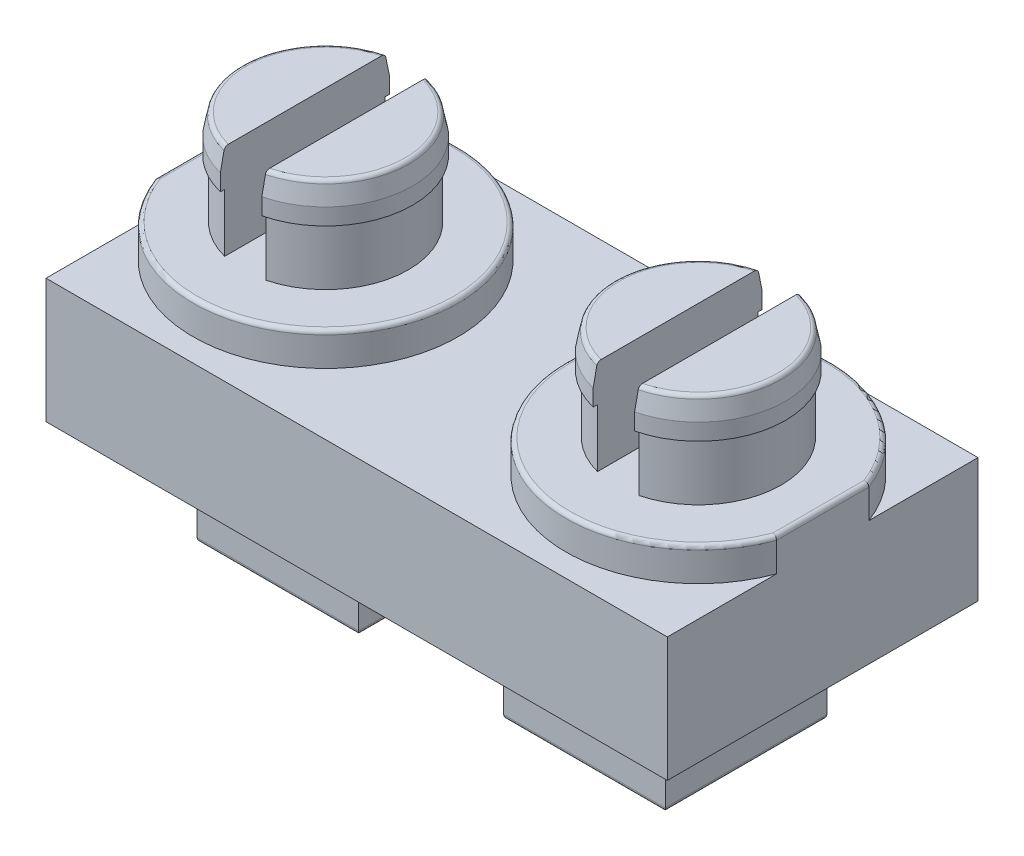
SolidWorks part; units mm, degrees
ref_plane "前视基准面" through (0, 0, 0) normal (0, 0, 1) x (1, 0, 0)
ref_plane "上视基准面" through (0, 0, 0) normal (0, 1, 0) x (1, 0, 0)
ref_plane "右视基准面" through (0, 0, 0) normal (1, 0, 0) x (0, 0, -1)
sketch "草图1" plane through (0, 0, 0) normal (0, 1, 0) x (1, 0, 0)
  line L0 (0, 0) -> (7.5, 0) construction
  line L1 (0, -3.75) -> (0, 3.75)
  line L2 (0, 3.75) -> (7.5, 3.75)
  line L3 (7.5, 3.75) -> (7.5, -3.75)
  line L4 (0, -3.75) -> (7.5, -3.75)
  dimension "D1" = 7.5
  dimension "D2" = 3.75
extrude "凸台-拉伸1" add sketch "草图1" along normal blind 3
sketch "草图3" plane through (0, 0, 3.75) normal (0, 0, 1) x (1, 0, 0)
  line L0 (0, 0) -> (3.7, 0) construction
  line L1 (0, 0) -> (7.5, 0) construction
  line L2 (3.7, 0) -> (3.7, -2) construction
  line L3 (3.7, -2) -> (3.7, -2.5) construction
  line L4 (5.2, 0) -> (2.2, 0)
  line L5 (2.2, 0) -> (2.2, -0.6771)
  line L6 (5.65, -2.5) -> (1.75, -2.5)
  line L7 (1.75, -2.5) -> (1.75, -1.5556)
  line L8 (5.65, -2.5) -> (5.65, -1.5556)
  line L9 (5.2, 0) -> (5.2, -0.6771)
  arc A0 (2.2, -0.6771) -> (1.75, -1.5556) centre (3.7, -2) ccw
  arc A1 (5.65, -1.5556) -> (5.2, -0.6771) centre (3.7, -2) ccw
  dimension "D1" = 3.7
  dimension "D2" = 2
  dimension "D3" = 0.5
  dimension "D4" = 1.5
  dimension "D5" = 1.95
extrude "凸台-拉伸2" add sketch "草图3" against normal blind 7.5
sketch "草图4" plane through (7.5, 0, 0) normal (1, 0, 0) x (0, 0, -1)
  line L0 (0, 0) -> (0, -2) construction
  line L1 (0, -2) -> (0, -2.5) construction
  line L2 (3.75, -2.5) -> (-3.75, -2.5) construction
  line L3 (1.5, 0) -> (3.75, 0)
  line L4 (-3.75, 0) -> (3.75, 0) construction
  line L5 (-1.5, 0) -> (-1.5, -0.6771)
  line L7 (-1.95, -2.5) -> (-1.95, -1.5556)
  line L8 (1.95, -2.5) -> (1.95, -1.5556)
  line L9 (1.5, 0) -> (1.5, -0.6771)
  line L10 (1.95, -2.5) -> (3.75, -2.5)
  line L11 (-3.75, 0) -> (-1.5, 0)
  line L12 (-3.75, 0) -> (-3.75, -2.5)
  line L13 (-3.75, -2.5) -> (-1.95, -2.5)
  line L14 (3.75, 0) -> (3.75, -2.5)
  arc A0 (-1.5, -0.6771) -> (-1.95, -1.5556) centre (0, -2) ccw
  arc A1 (1.95, -1.5556) -> (1.5, -0.6771) centre (0, -2) ccw
  dimension "D1" = 2
  dimension "D2" = 1.5
  dimension "D3" = 1.95
extrude "切除-拉伸1" cut sketch "草图4" against normal blind 7.5
sketch "草图5" plane through (0, 3, 0) normal (0, 1, 0) x (1, 0, 0)
  line L0 (0, 0) -> (4.5, 0) construction
  circle A0 centre (4.5, 0) radius 3.2
  dimension "D2" = 6.4
  dimension "D1" = 4.5
extrude "凸台-拉伸3" add sketch "草图5" along normal blind 0.8
sketch "草图6" plane through (0, 3.8, 0) normal (0, 1, 0) x (1, 0, 0)
  circle A0 centre (4.5, 0) radius 2
  dimension "D1" = 4
extrude "凸台-拉伸4" add sketch "草图6" along normal blind 2.3
sketch "草图7" plane through (0, 0, 0) normal (0, 0, 1) x (1, 0, 0)
  line L0 (2.5, 6.1) -> (2.5, 5.2)
  line L1 (2.5, 6.1) -> (2.5, 3.8) construction
  line L2 (2.5, 5.2) -> (2.4, 5.2)
  line L3 (2.4, 5.2) -> (2.4, 5.6)
  line L4 (2.4, 5.6) -> (2.5, 6.1)
  line L5 (4.5, 6.1) -> (4.5, 3.8) construction
  line L6 (6.5, 6.1) -> (2.5, 6.1) construction
  line L7 (7.7, 3.8) -> (1.3, 3.8) construction
  dimension "D1" = 0.9
  dimension "D2" = 0.1
  dimension "D3" = 0.4
revolve "旋转1" add sketch "草图7" angle 360 about L5
sketch "草图8" plane through (0, 6.1, 0) normal (0, 1, 0) x (1, 0, 0)
  line L0 (4.5, 0) -> (5, 0) construction
  line L1 (5, -3) -> (5, 3)
  line L2 (5, 3) -> (4, 3)
  line L3 (4.5, 3) -> (4.5, -3) construction
  line L4 (5, -3) -> (4, -3)
  line L5 (4, -3) -> (4, 3)
  dimension "D1" = 0.5
  dimension "D2" = 3
extrude "切除-拉伸2" cut sketch "草图8" against normal blind 2.3
sketch "草图9" plane through (0, 3, 0) normal (0, 1, 0) x (1, 0, 0)
  line L0 (7.5, 3.75) -> (7.5, -3.75)
  line L1 (7.5, -3.75) -> (8.5186, -3.75)
  line L2 (8.5186, -3.75) -> (8.5186, 3.75)
  line L3 (8.5186, 3.75) -> (7.5, 3.75)
extrude "切除-拉伸5" cut sketch "草图9" along normal blind 0.8
fillet "圆角2" radius 0.1 8 edges at (5.65, -2.5, 0) (3.7, -2.5, -1.95) (1.75, -2.5, 0) (3.7, -2.5, 1.95) (7.5, 3.8, 0) (1.3, 3.8, 0) (2.5, 6.1, 0) (6.5, 6.1, 0)
mirror "镜向1" about plane through (0, 0, 0) normal (1, 0, 0) of "切除-拉伸5", "切除-拉伸2", "旋转1", "凸台-拉伸4", "凸台-拉伸3", "切除-拉伸1", "凸台-拉伸2", "凸台-拉伸1", "圆角2"
